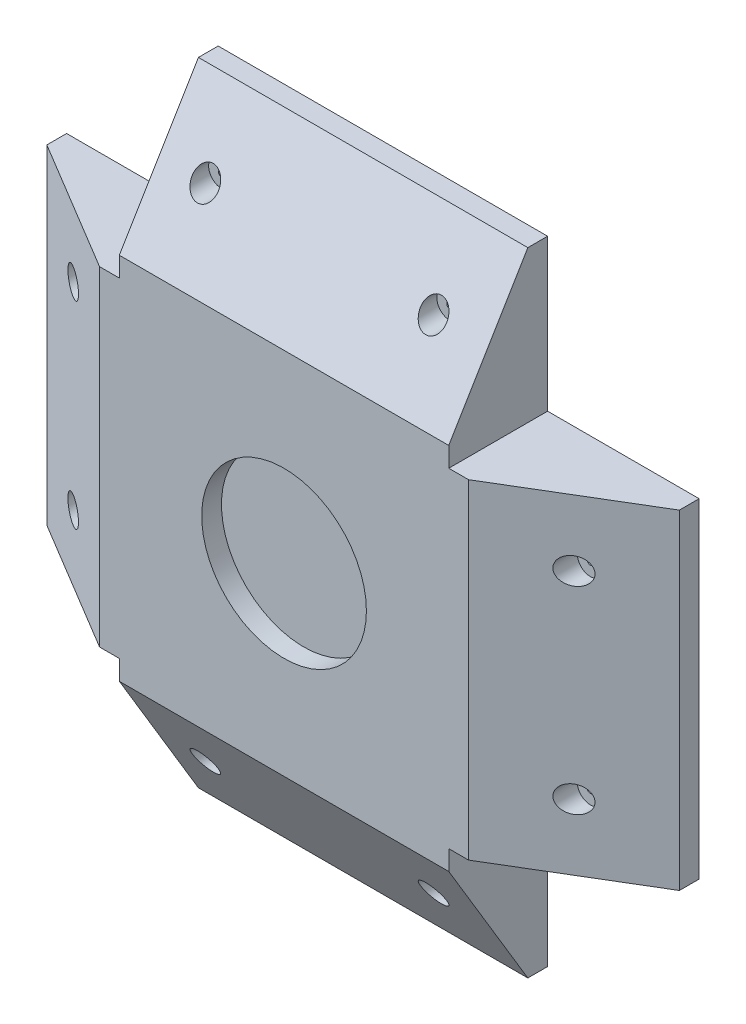
SolidWorks part; units mm, degrees
ref_plane "Plan de face" through (0, 0, 0) normal (0, 0, 1) x (1, 0, 0)
ref_plane "Plan de dessus" through (0, 0, 0) normal (0, 1, 0) x (1, 0, 0)
ref_plane "Plan de droite" through (0, 0, 0) normal (1, 0, 0) x (0, 0, -1)
sketch "Esquisse1" plane through (0, 0, 0) normal (0, 0, 1) x (1, 0, 0)
  line L1 (-50, -50) -> (50, -50)
  line L2 (-50, -50) -> (-50, 50)
  line L3 (-50, 50) -> (50, 50)
  line L4 (50, -50) -> (50, 50)
  dimension "D1" = 100
  dimension "D2" = 100
  dimension "D3" = 50
  dimension "D4" = 50
extrude "Boss.-Extru.1" add sketch "Esquisse1" along normal blind 6
sketch "Esquisse2" plane through (-50, 0, 0) normal (-1, 0, 0) x (0, 0, 1)
  line L0 (6, 50) -> (6, -50)
  line L1 (6, 50) -> (-24, 50)
  line L2 (6, -50) -> (-24, -50)
  line L3 (-24, 50) -> (-24, -50)
  dimension "D1" = 30
extrude "Boss.-Extru.2" add sketch "Esquisse2" along normal blind 6
sketch "Esquisse3" plane through (50, 0, 0) normal (1, 0, 0) x (0, 0, -1)
  line L0 (-6, -50) -> (-6, 50)
  line L1 (-6, -50) -> (24, -50)
  line L2 (-6, 50) -> (24, 50)
  line L3 (24, -50) -> (24, 50)
  dimension "D1" = 30
extrude "Boss.-Extru.3" add sketch "Esquisse3" along normal blind 6
sketch "Esquisse4" plane through (56, 0, 0) normal (1, 0, 0) x (0, 0, -1)
  line L0 (24, 50) -> (24, -50)
  line L1 (24, 50) -> (18, 50)
  line L2 (24, -50) -> (18, -50)
  line L3 (18, 50) -> (18, -50)
  dimension "D1" = 6
extrude "Boss.-Extru.4" add sketch "Esquisse4" along normal blind 40
sketch "Esquisse5" plane through (-56, 0, 0) normal (-1, 0, 0) x (0, 0, 1)
  line L0 (-24, 50) -> (-24, -50)
  line L1 (-24, 50) -> (-18, 50)
  line L2 (-24, -50) -> (-18, -50)
  line L3 (-18, 50) -> (-18, -50)
  dimension "D1" = 6
extrude "Boss.-Extru.5" add sketch "Esquisse5" along normal blind 40
sketch "Esquisse6" plane through (0, 50, 0) normal (0, 1, 0) x (1, 0, 0)
  line L0 (-56, -6) -> (-56, 18)
  line L1 (-56, 18) -> (-96, 18)
  line L2 (-96, 18) -> (-56, -6)
extrude "Boss.-Extru.7" add sketch "Esquisse6" against normal blind 100
sketch "Esquisse8" plane through (0, -50, 0) normal (0, -1, 0) x (-1, 0, 0)
  line L0 (-56, -6) -> (-96, 18)
  line L1 (-96, 18) -> (-56, 18)
  line L2 (-56, 18) -> (-56, -6)
extrude "Boss.-Extru.8" add sketch "Esquisse8" against normal blind 100
sketch "Esquisse9" plane through (0, 0, -24) normal (0, 0, -1) x (-1, 0, 0)
  line L0 (-76, 66.0927) -> (-76, -69.5356) construction
  line L1 (-96, -50) -> (-96, 50) construction
  line L2 (0, 75.5176) -> (0, -97.317) construction
  line L3 (-96, 50) -> (-50, 50) construction
  line L4 (-96, -50) -> (-50, -50) construction
  circle A0 centre (-76, 30) radius 1
  circle A1 centre (-76, -30) radius 1
  circle A2 centre (76, -30) radius 1
  circle A3 centre (76, 30) radius 1
  dimension "D2" = 2
  dimension "D3" = 2
  dimension "D4" = 20
  dimension "D5" = 20
  dimension "D1" = 20
extrude "Enlèv. mat.-Extru.1" cut sketch "Esquisse9" against normal blind 60
sketch "Esquisse10" plane through (0, 0, 6) normal (0, 0, 1) x (1, 0, 0)
  line L0 (76, 76.0822) -> (76, -67.6877) construction
  line L1 (96, 50) -> (96, -50) construction
  line L4 (0, 58.8529) -> (0, -69.7243) construction
  circle A0 centre (76, 30) radius 4
  circle A1 centre (76, -30) radius 4
  circle A2 centre (-76, -30) radius 4
  circle A3 centre (-76, 30) radius 4
  dimension "D2" = 8
  dimension "D3" = 8
  dimension "D1" = 20
extrude "Enlèv. mat.-Extru.2" cut sketch "Esquisse10" against normal blind 17
sketch "Esquisse28" plane through (0, -50, 0) normal (0, -1, 0) x (-1, 0, 0)
  line L0 (50, 24) -> (-50, 24)
  line L1 (50, 24) -> (50, -6)
  line L2 (-50, 24) -> (-50, -6)
  line L3 (50, -6) -> (-50, -6)
  line L4 (56, -6) -> (-56, -6) construction
extrude "Boss.-Extru.27" add sketch "Esquisse28" along normal blind 6 and the other way blind 3
sketch "Esquisse29" plane through (0, -56, 0) normal (0, -1, 0) x (-1, 0, 0)
  line L0 (50, 24) -> (-50, 24)
  line L1 (50, 24) -> (50, 18)
  line L2 (-50, 24) -> (-50, 18)
  line L3 (50, 18) -> (-50, 18)
  dimension "D1" = 6
extrude "Boss.-Extru.28" add sketch "Esquisse29" along normal blind 40
sketch "Esquisse30" plane through (0, 50, 0) normal (0, 1, 0) x (1, 0, 0)
  line L0 (50, 24) -> (-50, 24)
  line L1 (50, 24) -> (50, -6)
  line L2 (-50, 24) -> (-50, -6)
  line L3 (50, -6) -> (-50, -6)
  line L4 (56, -6) -> (-56, -6) construction
extrude "Boss.-Extru.30" add sketch "Esquisse30" along normal blind 6 and the other way blind 3
sketch "Esquisse31" plane through (0, 56, 0) normal (0, 1, 0) x (1, 0, 0)
  line L0 (-50, 24) -> (50, 24)
  line L1 (-50, 24) -> (-50, 18)
  line L2 (50, 24) -> (50, 18)
  line L3 (-50, 18) -> (50, 18)
  line L4 (50, -6) -> (50, 24) construction
  line L5 (50, 24) -> (50, -6) construction
  line L6 (50, 24) -> (-50, 24) construction
  dimension "D1" = 6
extrude "Boss.-Extru.31" add sketch "Esquisse31" along normal blind 40
sketch "Esquisse32" plane through (-50, 0, 0) normal (-1, 0, 0) x (0, 0, 1)
  line L0 (-18, -56) -> (6, -56)
  line L1 (6, -56) -> (-18, -96)
  line L2 (-18, -96) -> (-18, -56)
extrude "Boss.-Extru.32" add sketch "Esquisse32" against normal blind 100
sketch "Esquisse33" plane through (-50, 0, 0) normal (-1, 0, 0) x (0, 0, 1)
  line L0 (-18, 56) -> (6, 56)
  line L1 (6, 56) -> (-18, 96)
  line L2 (-18, 96) -> (-18, 56)
extrude "Boss.-Extru.33" add sketch "Esquisse33" against normal blind 100
sketch "Esquisse34" plane through (0, 0, 6) normal (0, 0, 1) x (1, 0, 0)
  line L0 (147.3278, 0) -> (-142.324, 0) construction
  line L1 (-147.7684, -76) -> (214.544, -76) construction
  line L2 (50, -96) -> (-50, -96) construction
  circle A0 centre (-35.8922, -76) radius 1
  circle A1 centre (33.3878, -76) radius 1
  circle A2 centre (33.3878, 76) radius 1
  circle A3 centre (-35.8922, 76) radius 1
  dimension "D2" = 2
  dimension "D3" = 2
  dimension "D1" = 20
extrude "Enlèv. mat.-Extru.7" cut sketch "Esquisse34" against normal blind 100
sketch "Esquisse35" plane through (0, 0, 6) normal (0, 0, 1) x (1, 0, 0)
  line L0 (80.2099, -76) -> (-99.1415, -76) construction
  line L1 (-50, -96) -> (50, -96) construction
  line L2 (-148.1016, 0) -> (141.4268, 0) construction
  circle A0 centre (33.3878, -76) radius 4
  circle A1 centre (-35.8922, -76) radius 4
  circle A2 centre (-35.8922, 76) radius 4
  circle A3 centre (33.3878, 76) radius 4
  dimension "D2" = 8
  dimension "D3" = 8
  dimension "D1" = 20
extrude "Enlèv. mat.-Extru.8" cut sketch "Esquisse35" against normal blind 17
sketch "Esquisse36" plane through (0, 0, 6) normal (0, 0, 1) x (1, 0, 0)
  circle A0 centre (0, 0) radius 25
  dimension "D1" = 50
extrude "Enlèv. mat.-Extru.9" cut sketch "Esquisse36" against normal blind 6
sketch "Esquisse37" plane through (0, 0, -24) normal (0, 0, -1) x (-1, 0, 0)
  line L0 (50, -47) -> (-50, -47)
  line L1 (50, -47) -> (50, 47.1108)
  line L2 (-50, -47) -> (-50, 47.1108)
  line L3 (50, 47.1108) -> (-50, 47.1108)
extrude "Boss.-Extru.34" add sketch "Esquisse37" against normal up to surface (24 mm away) up to face at (25, 0, 0)
